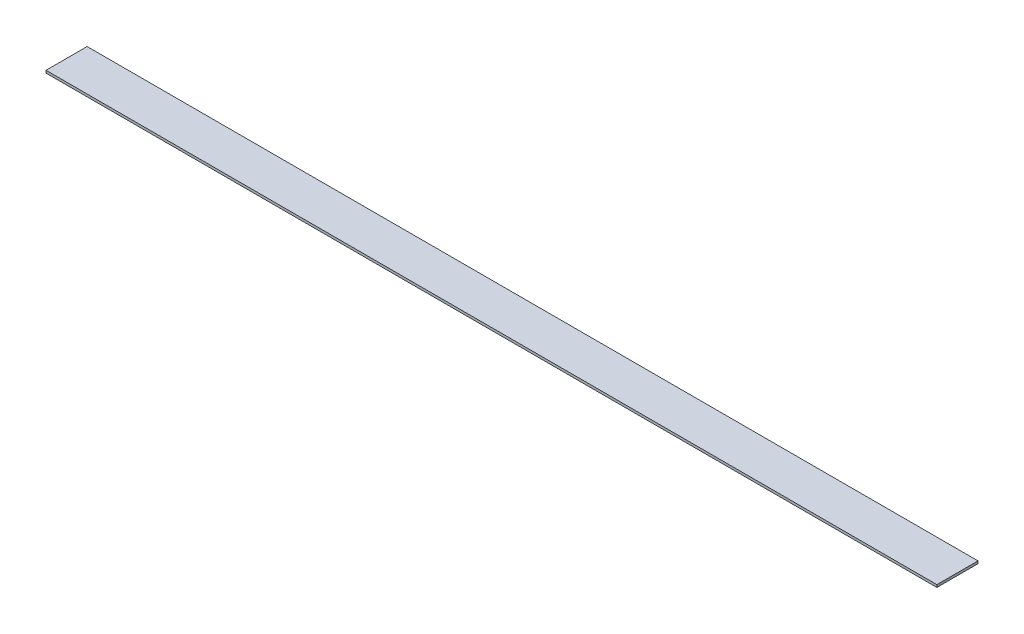
SolidWorks part; units mm, degrees
ref_plane "Front Plane" through (0, 0, 0) normal (0, 0, 1) x (1, 0, 0)
ref_plane "Top Plane" through (0, 0, 0) normal (0, 1, 0) x (1, 0, 0)
ref_plane "Right Plane" through (0, 0, 0) normal (1, 0, 0) x (0, 0, -1)
sketch "Sketch1" plane through (0, 0, 0) normal (0, 1, 0) x (1, 0, 0)
  line L1 (-541.5, 25) -> (541.5, 25)
  line L2 (-541.5, 25) -> (-541.5, -25)
  line L3 (-541.5, -25) -> (541.5, -25)
  line L4 (541.5, 25) -> (541.5, -25)
  line L5 (-541.5, 25) -> (541.5, -25) construction
  line L6 (-541.5, -25) -> (541.5, 25) construction
  point P0 (0, 0)
  dimension "D1" = 1083
  dimension "D2" = 50
extrude "Boss-Extrude1" add sketch "Sketch1" along normal blind 3
